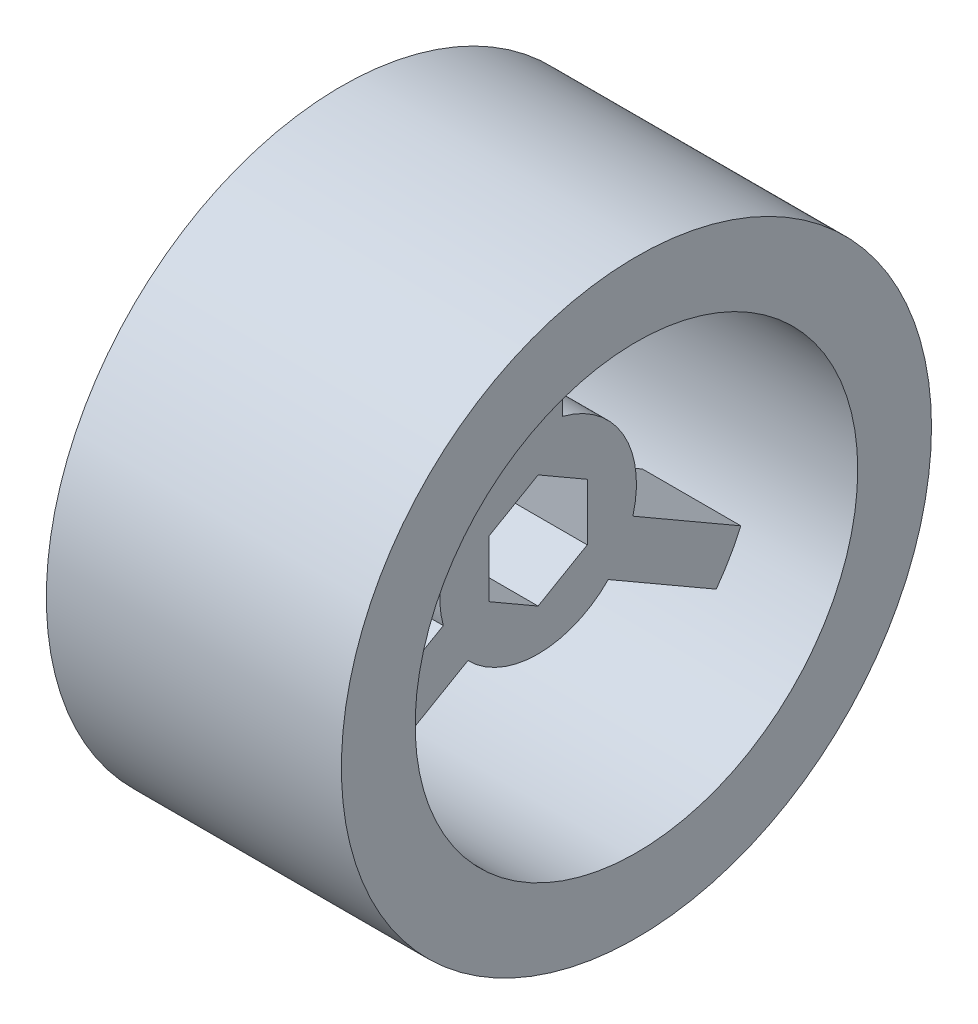
SolidWorks part; units mm, degrees
material "Plain Carbon Steel"
ref_plane "Front Plane" through (0, 0, 0) normal (0, 0, 1) x (1, 0, 0)
ref_plane "Top Plane" through (0, 0, 0) normal (0, 1, 0) x (1, 0, 0)
ref_plane "Right Plane" through (0, 0, 0) normal (1, 0, 0) x (0, 0, -1)
sketch "Sketch1" plane through (0, 0, 0) normal (1, 0, 0) x (0, 0, -1)
  line L0 (0, 0) -> (1.1614, 0) construction
  line L1 (0, 0) -> (0, 38.1) construction
  line L2 (0, 0) -> (32.9956, -19.05) construction
  line L3 (0, 0) -> (-32.9956, -19.05) construction
  line L4 (-3.175, 28.3981) -> (-3.175, 12.2967)
  line L5 (3.175, 28.3981) -> (3.175, 12.2967)
  line L6 (26.1809, -11.4494) -> (12.2368, -3.3987)
  line L7 (23.0059, -16.9487) -> (9.0618, -8.898)
  line L8 (-23.0059, -16.9487) -> (-9.0618, -8.898)
  line L9 (-26.1809, -11.4494) -> (-12.2368, -3.3987)
  arc A0 (-9.0618, -8.898) -> (9.0618, -8.898) centre (0, 0) ccw
  circle A1 centre (0, 0) radius 38.1 construction
  arc A2 (-23.0059, -16.9487) -> (23.0059, -16.9487) centre (0, 0) ccw
  circle A3 centre (0, 0) radius 28.575 construction
  arc A4 (12.2368, -3.3987) -> (3.175, 12.2967) centre (0, 0) ccw
  arc A5 (-3.175, 12.2967) -> (-12.2368, -3.3987) centre (0, 0) ccw
  arc A6 (-3.175, 28.3981) -> (-26.1809, -11.4494) centre (0, 0) ccw
  arc A7 (26.1809, -11.4494) -> (3.175, 28.3981) centre (0, 0) ccw
  circle A8 centre (0, 0) radius 28.575
  point P9 (0, 0)
  point P25 (0, 0)
  dimension "D1" = 25.4
  dimension "D2" = 38.1
  dimension "D5" = 3.175
  dimension "D4" = 9.525
  dimension "D3" = 3
  dimension "D6" = 3
extrude "Boss-Extrude1" add sketch "Sketch1" along normal blind 12.7 contours L5 A8 L4 A5 L9 L8 A0 L7 L6 A4
ref_plane "Plane1" through (25.4, 0, 0) normal (1, 0, 0) x (0, 0, -1)
sketch "Sketch2" plane through (25.4, 0, 0) normal (1, 0, 0) x (0, 0, -1)
  circle A0 centre (0, 0) radius 38.1
  circle A1 centre (0, 0) radius 28.575
  dimension "D1" = 76.2
extrude "Boss-Extrude2" add sketch "Sketch2" against normal blind 38.1
sketch "Sketch3" plane through (12.7, 0, 0) normal (1, 0, 0) x (0, 0, -1)
  line L1 (0, 7.3323) -> (-6.35, 3.6662)
  line L2 (-6.35, 3.6662) -> (-6.35, -3.6662)
  line L3 (-6.35, -3.6662) -> (0, -7.3323)
  line L4 (0, -7.3323) -> (6.35, -3.6662)
  line L5 (6.35, -3.6662) -> (6.35, 3.6662)
  line L6 (6.35, 3.6662) -> (0, 7.3323)
  circle A0 centre (0, 0) radius 6.35 construction
  dimension "D1" = 12.7
extrude "Cut-Extrude1" cut sketch "Sketch3" against normal blind 38.1
